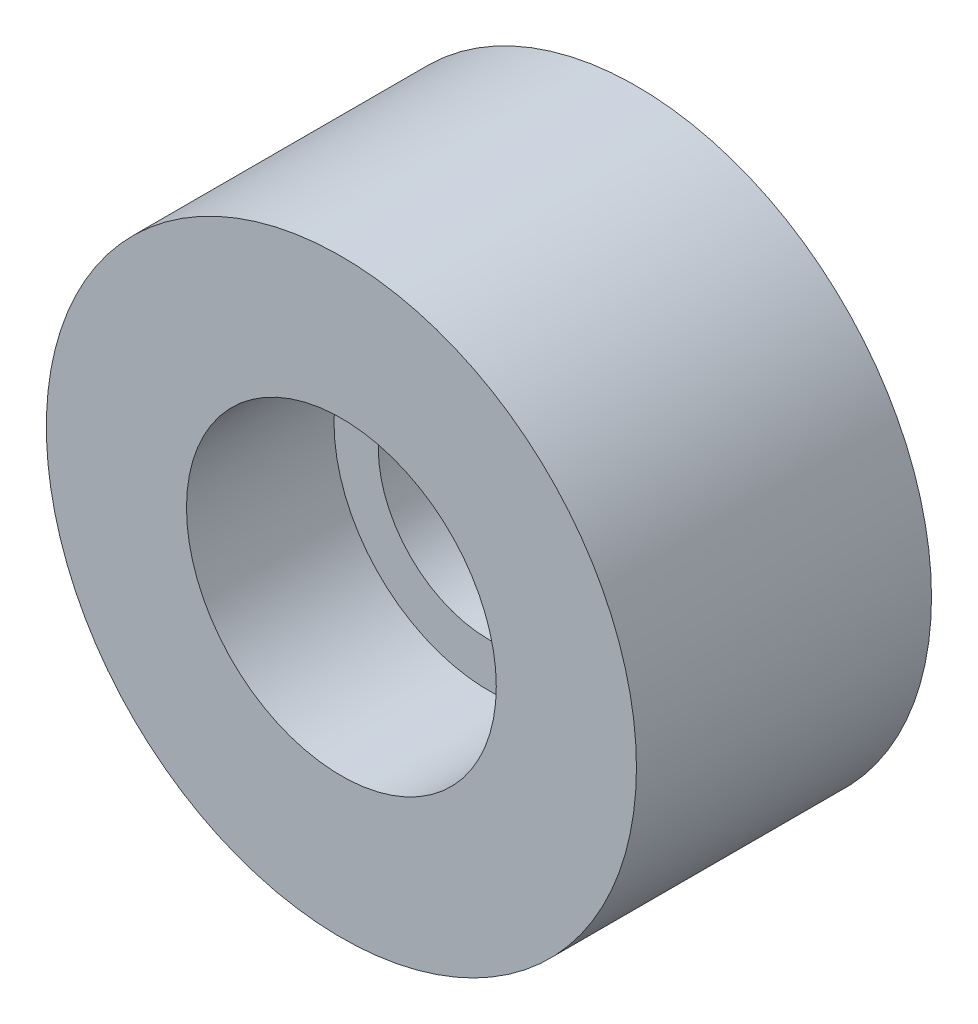
SolidWorks part; units mm, degrees
ref_plane "Plan de face" through (0, 0, 0) normal (0, 0, 1) x (1, 0, 0)
ref_plane "Plan de dessus" through (0, 0, 0) normal (0, 1, 0) x (1, 0, 0)
ref_plane "Plan de droite" through (0, 0, 0) normal (1, 0, 0) x (0, 0, -1)
sketch "Esquisse1" plane through (0, 0, 0) normal (0, 0, 1) x (1, 0, 0)
  circle A0 centre (0, 0) radius 4
  dimension "D1" = 8
extrude "Boss.-Extru.1" add sketch "Esquisse1" along normal blind 4
sketch "Esquisse2" plane through (0, 0, 4) normal (0, 0, 1) x (1, 0, 0)
  circle A0 centre (0, 0) radius 2.1
  dimension "D1" = 4.2
extrude "Enlèv. mat.-Extru.1" cut sketch "Esquisse2" against normal blind 2
sketch "Esquisse3" plane through (0, 0, 0) normal (0, 0, -1) x (-1, 0, 0)
  circle A0 centre (0, 0) radius 1.5
  dimension "D1" = 3
extrude "Enlèv. mat.-Extru.2" cut sketch "Esquisse3" against normal through all
